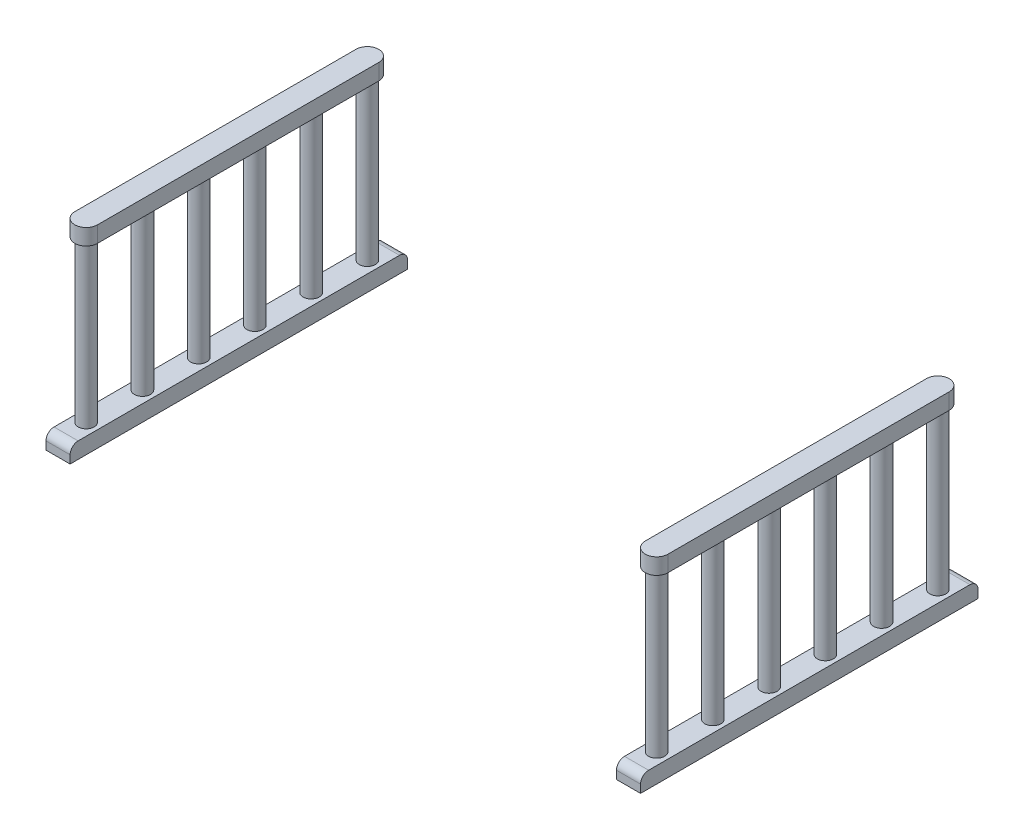
SolidWorks part; units mm, degrees
ref_plane "Front Plane" through (0, 0, 0) normal (0, 0, 1) x (1, 0, 0)
ref_plane "Top Plane" through (0, 0, 0) normal (0, 1, 0) x (1, 0, 0)
ref_plane "Right Plane" through (0, 0, 0) normal (1, 0, 0) x (0, 0, -1)
sketch "Sketch2" plane through (0, 0, 0) normal (0, 1, 0) x (1, 0, 0)
  line L0 (0, -12.024) -> (0, 987.976) construction
  line L1 (-1850, -12.024) -> (1850, -12.024) construction
  line L2 (1850, -12.024) -> (1700, -12.024)
  line L3 (-1850, -12.024) -> (-1700, -12.024)
  line L4 (-1850, -12.024) -> (-1850, 2087.976)
  line L5 (-1850, 2087.976) -> (-1700, 2087.976)
  line L6 (-1700, -12.024) -> (-1700, 2087.976)
  line L7 (1850, 2087.976) -> (1700, 2087.976)
  line L8 (1850, -12.024) -> (1850, 2087.976)
  line L9 (1700, -12.024) -> (1700, 2087.976)
  dimension "D1" = 1000
  dimension "D2" = 1850
  dimension "D3" = 2100
  dimension "D4" = 150
extrude "Boss-Extrude3" add sketch "Sketch2" along normal blind 100
ref_plane "Plane1" through (0, 100, 0) normal (0, 1, 0) x (1, 0, 0)
sketch "Sketch3" plane through (0, 100, 0) normal (0, 1, 0) x (1, 0, 0)
  line L0 (0, 0) -> (0, 2142.9852) construction
  line L1 (-1775, -12.024) -> (-1775, 162.976) construction
  line L2 (-1850, -12.024) -> (-1700, -12.024) construction
  circle A0 centre (-1775, 162.976) radius 50
  dimension "D2" = 100
  dimension "D1" = 175
extrude "Boss-Extrude4" add sketch "Sketch3" along normal blind 1000
pattern_linear "LPattern1" count 6 spacing 350 along (0, 0, -1) of "Boss-Extrude4"
ref_plane "Plane2" through (1700, 100, 12.024) normal (1, 0, 0) x (0, 0, -1)
sketch "Sketch5" plane through (0, 100, 0) normal (0, 1, 0) x (1, 0, 0)
  line L0 (1775, 2087.976) -> (1775, 1912.976) construction
  line L1 (1850, 2087.976) -> (1700, 2087.976) construction
  circle A0 centre (1775, 1912.976) radius 50
  dimension "D2" = 100
  dimension "D1" = 175
extrude "Boss-Extrude5" add sketch "Sketch5" along normal blind 1000
pattern_linear "LPattern2" count 6 spacing 350 along (0, 0, 1) of "Boss-Extrude5"
ref_plane "Plane3" through (0, 1100, 0) normal (0, 1, 0) x (1, 0, 0)
fillet "Fillet1" radius 50 1 edges at (-1775, 100, -2087.976)
fillet "Fillet2" radius 50 1 edges at (-1775, 100, 12.024)
fillet "Fillet3" radius 50 1 edges at (1775, 100, 12.024)
fillet "Fillet4" radius 50 1 edges at (1775, 100, -2087.976)
sketch "Sketch13" plane through (0, 1100, 0) normal (0, 1, 0) x (1, 0, 0)
  line L0 (-1775, 162.976) -> (-1775, 1912.976) construction
  line L1 (-1845.8383, 162.976) -> (-1845.8383, 1912.976)
  line L2 (-1704.1617, 162.976) -> (-1704.1617, 1912.976)
  line L3 (0, 0) -> (0, 2341.2867) construction
  line L4 (0, -605) -> (0, 605) construction
  line L5 (1775, 162.976) -> (1775, 1912.976) construction
  line L6 (1845.8383, 162.976) -> (1845.8383, 1912.976)
  line L7 (1704.1617, 162.976) -> (1704.1617, 1912.976)
  arc A0 (-1845.8383, 162.976) -> (-1704.1617, 162.976) centre (-1775, 162.976) ccw
  arc A1 (-1704.1617, 1912.976) -> (-1845.8383, 1912.976) centre (-1775, 1912.976) ccw
  arc A2 (1845.8383, 162.976) -> (1704.1617, 162.976) centre (1775, 162.976) cw
  arc A3 (1704.1617, 1912.976) -> (1845.8383, 1912.976) centre (1775, 1912.976) cw
  point P4 (-1775, 1037.976)
  point P16 (1775, 1037.976)
extrude "Boss-Extrude8" add sketch "Sketch13" along normal blind 100
sketch "Sketch14" plane through (0, 1100, 0) normal (0, 1, 0) x (1, 0, 0)
  line L1 (-1899.1526, 2186.8784) -> (-1093.8951, 2186.8784)
  line L2 (-1899.1526, 2186.8784) -> (-1899.1526, -316.0877)
  line L3 (-1899.1526, -316.0877) -> (-1093.8951, -316.0877)
  line L4 (-1093.8951, 2186.8784) -> (-1093.8951, -316.0877)
